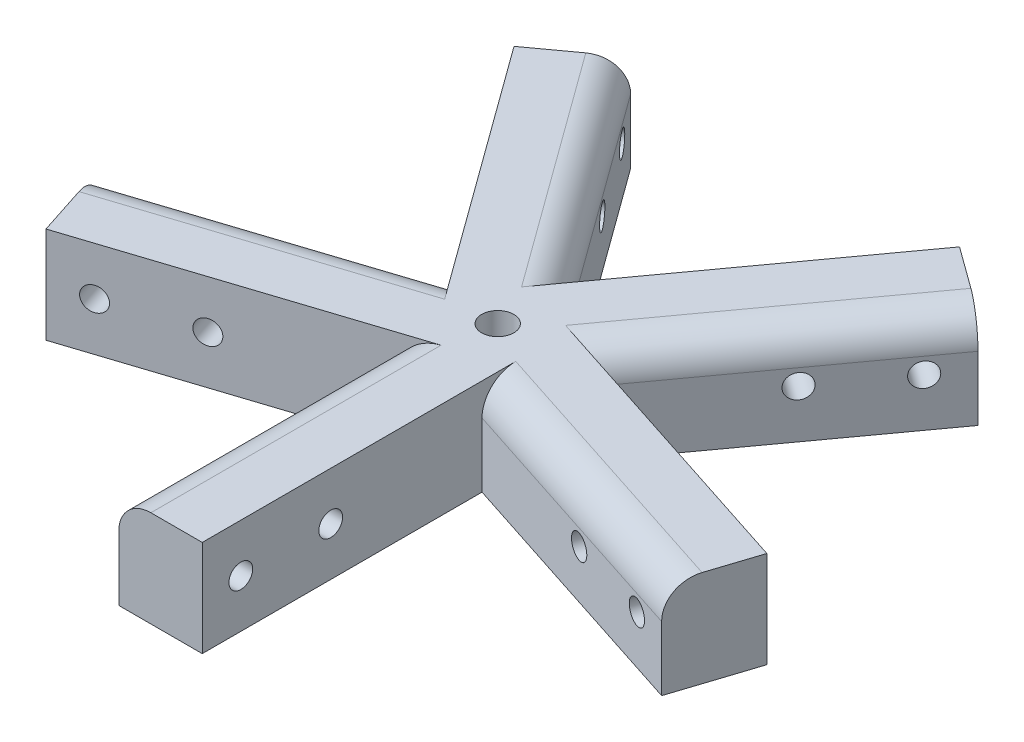
SolidWorks part; units mm, degrees
ref_plane "Front Plane" through (0, 0, 0) normal (0, 0, 1) x (1, 0, 0)
ref_plane "Top Plane" through (0, 0, 0) normal (0, 1, 0) x (1, 0, 0)
ref_plane "Right Plane" through (0, 0, 0) normal (1, 0, 0) x (0, 0, -1)
sketch "proto-pentagram" plane through (0, 0, 0) normal (0, 1, 0) x (1, 0, 0)
  line L0 (0, 52.5) -> (0, -52.5) construction
  line L1 (-52.5, 0) -> (52.5, 0) construction
  line L2 (-51.9391, -10.0415) -> (-10.5172, 3.4173)
  line L3 (-6.5, -52.5) -> (6.5, -52.5)
  line L4 (-6.5, -52.5) -> (-6.5, -8.9465)
  line L6 (6.5, -52.5) -> (6.5, -8.9465)
  line L8 (-47.9219, -22.4053) -> (-6.5, -8.9465)
  line L9 (-51.9391, -10.0415) -> (-47.9219, -22.4053)
  line L10 (-25.6001, 46.294) -> (0, 11.0585)
  line L12 (-36.1173, 38.6528) -> (-10.5172, 3.4173)
  line L13 (-25.6001, 46.294) -> (-36.1173, 38.6528)
  line L14 (36.1173, 38.6528) -> (10.5172, 3.4173)
  line L16 (25.6001, 46.294) -> (0, 11.0585)
  line L17 (36.1173, 38.6528) -> (25.6001, 46.294)
  line L18 (47.9219, -22.4053) -> (6.5, -8.9465)
  line L20 (51.9391, -10.0415) -> (10.5172, 3.4173)
  line L21 (47.9219, -22.4053) -> (51.9391, -10.0415)
  circle A0 centre (0, 0) radius 2.5
  circle A1 centre (0, 0) radius 7.5
  point P31 (0, 0)
  dimension "D1" = 5
  dimension "D2" = 15
  dimension "D3" = 105
  dimension "D4" = 105
  dimension "D6" = 6.5
  dimension "D7" = 13
  dimension "D8" = 5
extrude "Boss-Extrude1" add sketch "proto-pentagram" along normal blind 15 contours L18 L21 L20 L14 L17 L16 L10 L13 L12 L2 L9 L8 L4 L3 L6 A1 | A1 A0
sketch "pick-1" plane through (6.5, 0, 0) normal (1, 0, 0) x (0, 0, -1)
  line L0 (-52.5, 15) -> (-52.5, 0) construction
  circle A0 centre (-46.5, 7.5) radius 1.85
  circle A1 centre (-32.5, 7.5) radius 1.85
  dimension "D3" = 3.7
  dimension "D4" = 3.7
  dimension "D1" = 6
  dimension "D2" = 14
sketch "pick-2" plane through (2.0086, 0, -6.1819) normal (0.309, 0, -0.9511) x (-0.9511, 0, -0.309)
  line L0 (-52.5, 15) -> (-52.5, 0) construction
  circle A0 centre (-46.5, 7.5) radius 1.85
  circle A1 centre (-32.5, 7.5) radius 1.85
  dimension "D3" = 3.7
  dimension "D4" = 3.7
  dimension "D1" = 6
  dimension "D2" = 14
sketch "pick-3" plane through (-5.2586, 0, -3.8206) normal (-0.809, 0, -0.5878) x (-0.5878, 0, 0.809)
  line L0 (-52.5, 15) -> (-52.5, 0) construction
  circle A0 centre (-46.5, 7.5) radius 1.85
  circle A1 centre (-32.5, 7.5) radius 1.85
  dimension "D3" = 3.7
  dimension "D4" = 3.7
  dimension "D1" = 6
  dimension "D2" = 14
sketch "pick-4" plane through (-5.2586, 0, 3.8206) normal (-0.809, 0, 0.5878) x (0.5878, 0, 0.809)
  line L0 (-52.5, 15) -> (-52.5, 0) construction
  circle A0 centre (-46.5, 7.5) radius 1.85
  circle A1 centre (-32.5, 7.5) radius 1.85
  dimension "D1" = 3.7
  dimension "D2" = 3.7
  dimension "D3" = 6
  dimension "D4" = 14
sketch "pick-5" plane through (2.0086, 0, 6.1819) normal (0.309, 0, 0.9511) x (0.9511, 0, -0.309)
  line L0 (-52.5, 15) -> (-52.5, 0) construction
  circle A0 centre (-46.5, 7.5) radius 1.85
  circle A1 centre (-32.5, 7.5) radius 1.85
  dimension "D3" = 3.7
  dimension "D4" = 3.7
  dimension "D1" = 6
  dimension "D2" = 14
extrude "Cut-Extrude1" cut sketch "pick-1" against normal blind 15
extrude "Cut-Extrude2" cut sketch "pick-2" against normal blind 15
extrude "Cut-Extrude3" cut sketch "pick-3" against normal blind 15
extrude "Cut-Extrude4" cut sketch "pick-4" against normal blind 15
extrude "Cut-Extrude5" cut sketch "pick-5" against normal blind 15
fillet "Fillet1" radius 5 5 edges at (-6.5, 15, 30.7232) (27.2109, 15, 15.6759) (23.3173, 15, -21.035) (-12.8001, 15, -28.6762) (-31.2281, 15, 3.3121)
